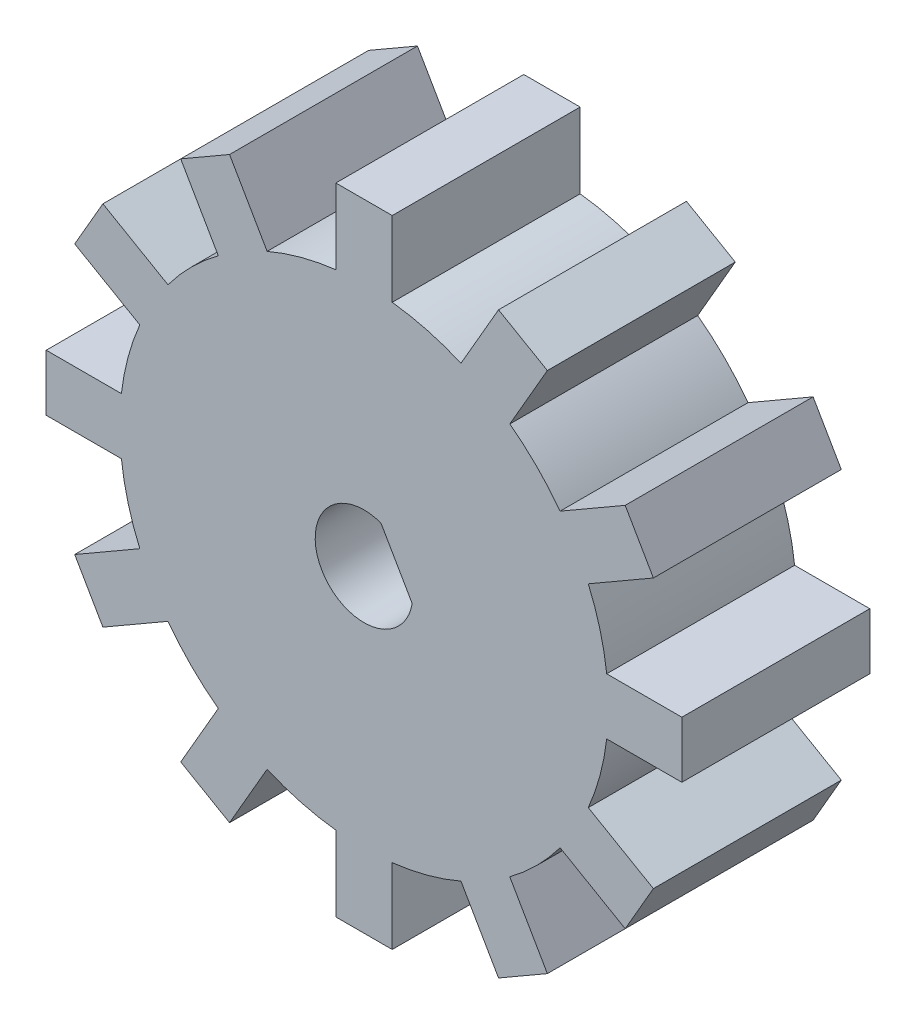
SolidWorks part; units mm, degrees
ref_plane "Front Plane" through (0, 0, 0) normal (0, 0, 1) x (1, 0, 0)
ref_plane "Top Plane" through (0, 0, 0) normal (0, 1, 0) x (1, 0, 0)
ref_plane "Right Plane" through (0, 0, 0) normal (1, 0, 0) x (0, 0, -1)
sketch "Sketch1" plane through (0, 0, 0) normal (0, 0, 1) x (1, 0, 0)
  line L0 (-1.5, 12.9132) -> (-1.5, 16.9132)
  line L1 (-1.5, 16.9132) -> (1.5, 16.9132)
  line L2 (1.5, 16.9132) -> (1.5, 12.9132)
  line L3 (0, 0) -> (0, 9.3747) construction
  line L4 (5.1575, 11.9331) -> (7.1575, 15.3972)
  line L5 (7.1575, 15.3972) -> (9.7556, 13.8972)
  line L6 (9.7556, 13.8972) -> (7.7556, 10.4331)
  line L7 (10.4331, 7.7556) -> (13.8972, 9.7556)
  line L8 (13.8972, 9.7556) -> (15.3972, 7.1575)
  line L9 (15.3972, 7.1575) -> (11.9331, 5.1575)
  line L10 (12.9132, 1.5) -> (16.9132, 1.5)
  line L11 (16.9132, 1.5) -> (16.9132, -1.5)
  line L12 (16.9132, -1.5) -> (12.9132, -1.5)
  line L13 (11.9331, -5.1575) -> (15.3972, -7.1575)
  line L14 (15.3972, -7.1575) -> (13.8972, -9.7556)
  line L15 (13.8972, -9.7556) -> (10.4331, -7.7556)
  line L16 (7.7556, -10.4331) -> (9.7556, -13.8972)
  line L17 (9.7556, -13.8972) -> (7.1575, -15.3972)
  line L18 (7.1575, -15.3972) -> (5.1575, -11.9331)
  line L19 (1.5, -12.9132) -> (1.5, -16.9132)
  line L20 (1.5, -16.9132) -> (-1.5, -16.9132)
  line L21 (-1.5, -16.9132) -> (-1.5, -12.9132)
  line L22 (-5.1575, -11.9331) -> (-7.1575, -15.3972)
  line L23 (-7.1575, -15.3972) -> (-9.7556, -13.8972)
  line L24 (-9.7556, -13.8972) -> (-7.7556, -10.4331)
  line L25 (-10.4331, -7.7556) -> (-13.8972, -9.7556)
  line L26 (-13.8972, -9.7556) -> (-15.3972, -7.1575)
  line L27 (-15.3972, -7.1575) -> (-11.9331, -5.1575)
  line L28 (-12.9132, -1.5) -> (-16.9132, -1.5)
  line L29 (-16.9132, -1.5) -> (-16.9132, 1.5)
  line L30 (-16.9132, 1.5) -> (-12.9132, 1.5)
  line L31 (-11.9331, 5.1575) -> (-15.3972, 7.1575)
  line L32 (-15.3972, 7.1575) -> (-13.8972, 9.7556)
  line L33 (-13.8972, 9.7556) -> (-10.4331, 7.7556)
  line L34 (-7.7556, 10.4331) -> (-9.7556, 13.8972)
  line L35 (-9.7556, 13.8972) -> (-7.1575, 15.3972)
  line L36 (-7.1575, 15.3972) -> (-5.1575, 11.9331)
  circle A0 centre (0, 0) radius 13
  point P31 (0, 0)
  point P56 (0, 0)
  dimension "D1" = 26
  dimension "D2" = 1.5
  dimension "D3" = 3
  dimension "D4" = 4
  dimension "D5" = 3
  dimension "D6" = 1.5
  dimension "D7" = 12
extrude "Boss-Extrude1" add sketch "Sketch1" along normal blind 10
sketch "Sketch2" plane through (0, 0, 10) normal (0, 0, 1) x (1, 0, 0)
  line L0 (2.5627, -0.4387) -> (0.9014, 2.4387)
  line L1 (1.7321, 1) -> (-2.2517, -1.3) construction
  line L2 (13.8972, 9.7556) -> (15.3972, 7.1575) construction
  arc A0 (0.9014, 2.4387) -> (2.5627, -0.4387) centre (0, 0) ccw
  dimension "D1" = 2.6
  dimension "D2" = 4.6
extrude "Cut-Extrude1" cut sketch "Sketch2" against normal blind 10
